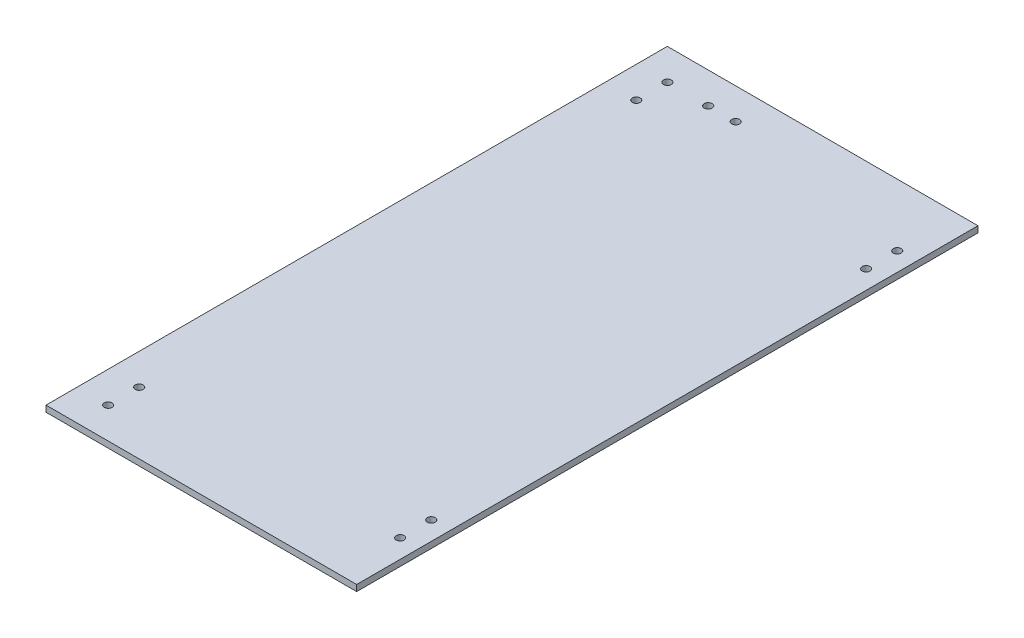
SolidWorks part; units mm, degrees
ref_plane "Front Plane" through (0, 0, 0) normal (0, 0, 1) x (1, 0, 0)
ref_plane "Top Plane" through (0, 0, 0) normal (0, 1, 0) x (1, 0, 0)
ref_plane "Right Plane" through (0, 0, 0) normal (1, 0, 0) x (0, 0, -1)
sketch "Sketch1" plane through (0, 0, 0) normal (0, 1, 0) x (1, 0, 0)
  line L1 (0, 0) -> (250, 0)
  line L2 (0, 0) -> (0, 500)
  line L3 (0, 500) -> (250, 500)
  line L4 (250, 0) -> (250, 500)
  dimension "D1" = 500
  dimension "D2" = 250
extrude "Boss-Extrude1" add sketch "Sketch1" along normal blind 5
sketch "Sketch2" plane through (0, 5, 0) normal (0, 1, 0) x (1, 0, 0)
  line L0 (0, 0) -> (250, 0) construction
  line L1 (0, 500) -> (0, 0) construction
  line L2 (250, 500) -> (0, 500) construction
  circle A0 centre (25, 25) radius 3.175
  circle A1 centre (25, 50) radius 3.175
  circle A2 centre (25, 475) radius 3.175
  circle A3 centre (25, 450) radius 3.175
  dimension "D3" = 6.35
  dimension "D1" = 25
  dimension "D2" = 25
  dimension "D4" = 25
  dimension "D5" = 25
  dimension "D6" = 25
extrude "Cut-Extrude1" cut sketch "Sketch2" against normal blind 10
sketch "Sketch4" plane through (0, 0, 0) normal (0, -1, 0) x (1, 0, 0)
  line L0 (125, 0) -> (125, -500)
  line L1 (0, 0) -> (250, 0) construction
  line L2 (250, -500) -> (0, -500) construction
  line L3 (250, -250) -> (0, -250)
  line L4 (250, 0) -> (250, -500) construction
  line L5 (0, -500) -> (0, 0) construction
  circle A0 centre (25, -475) radius 3.175 construction
  circle A1 centre (25, -450) radius 3.175 construction
  circle A2 centre (25, -25) radius 3.175 construction
  circle A3 centre (25, -50) radius 3.175 construction
  circle A4 centre (25, -475) radius 3.175
  circle A5 centre (25, -450) radius 3.175
  circle A6 centre (25, -25) radius 3.175
  circle A7 centre (25, -50) radius 3.175
  circle A8 centre (235, -50) radius 3.175
  circle A9 centre (235, -75) radius 3.175
  circle A10 centre (235, -425) radius 3.175
  circle A11 centre (235, -450) radius 3.175
  dimension "D1" = 6.35
  dimension "D2" = 6.35
  dimension "D3" = 50
  dimension "D4" = 25
  dimension "D5" = 15
extrude "Cut-Extrude3" cut sketch "Sketch4" against normal blind 10 contours A10 | A8 | A9 | A11
sketch "Sketch5" plane through (0, 5, 0) normal (0, 1, 0) x (1, 0, 0)
  line L0 (250, 500) -> (0, 500) construction
  line L1 (0, 500) -> (0, 0) construction
  circle A0 centre (80, 475) radius 3.175
  circle A1 centre (57.902, 475) radius 3.175
  dimension "D1" = 6.35
  dimension "D2" = 25
  dimension "D3" = 80
  dimension "D4" = 22.098
extrude "Cut-Extrude4" cut sketch "Sketch5" against normal blind 10
